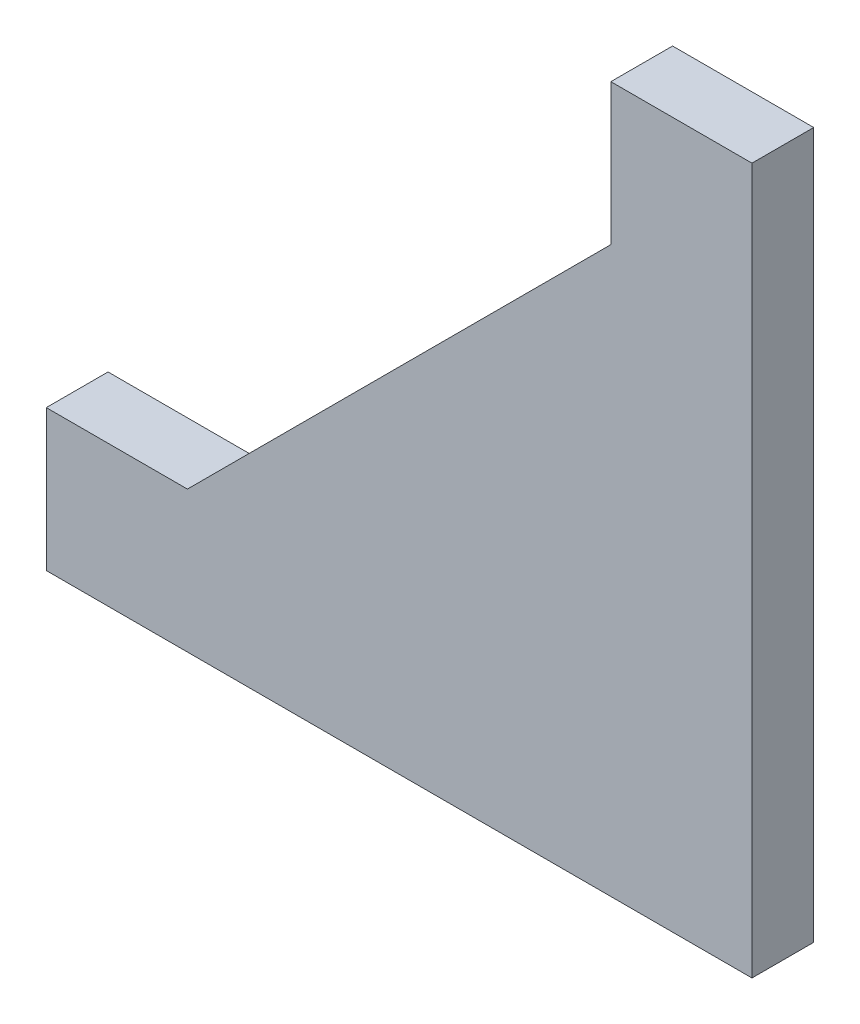
SolidWorks part; units mm, degrees
ref_plane "前视基准面" through (0, 0, 0) normal (0, 0, 1) x (1, 0, 0)
ref_plane "上视基准面" through (0, 0, 0) normal (0, 1, 0) x (1, 0, 0)
ref_plane "右视基准面" through (0, 0, 0) normal (1, 0, 0) x (0, 0, -1)
sketch "草图1" plane through (0, 0, 0) normal (0, 0, 1) x (1, 0, 0)
  line L0 (0, 0) -> (-40, 0)
  line L1 (0, 0) -> (0, 40)
  line L2 (-40, 0) -> (-40, 8)
  line L3 (-40, 8) -> (-32, 8)
  line L4 (0, 40) -> (-8, 40)
  line L5 (-8, 40) -> (-8, 32)
  line L6 (-8, 32) -> (-32, 8)
extrude "凸台-拉伸1" add sketch "草图1" along normal blind 3.5
